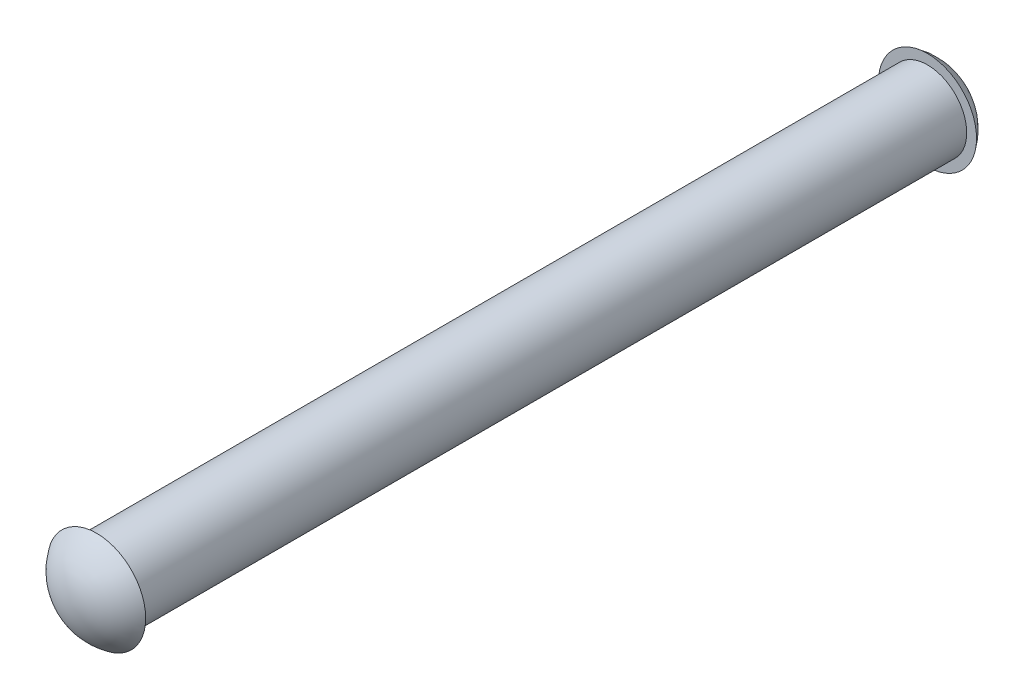
SolidWorks part; units mm, degrees
ref_plane "Alzado" through (0, 0, 0) normal (0, 0, 1) x (1, 0, 0)
ref_plane "Planta" through (0, 0, 0) normal (0, 1, 0) x (1, 0, 0)
ref_plane "Vista lateral" through (0, 0, 0) normal (1, 0, 0) x (0, 0, -1)
sketch "Croquis1" plane through (0, 0, 0) normal (0, 0, 1) x (1, 0, 0)
  circle A0 centre (0, 0) radius 1.2
  dimension "D1" = 2.4
extrude "Saliente-Extruir1" add sketch "Croquis1" along normal mid plane 25.4
sketch "Croquis4" plane through (0, 0, 0) normal (0, 1, 0) x (1, 0, 0)
  line L0 (0, -13.5) -> (0, -12.7)
  line L1 (-1.2, -12.7) -> (1.2, -12.7) construction
  line L2 (0, -12.7) -> (-1.5, -12.7)
  arc A0 (-1.5, -12.7) -> (0, -13.5) centre (0, -11.6938) ccw
  dimension "D2" = 0.8
  dimension "D1" = 1.5
revolve "Revolución1" add sketch "Croquis4" angle 360 about L0
mirror "Simetría1" about plane through (0, 0, 0) normal (0, 0, 1) of "Revolución1"
